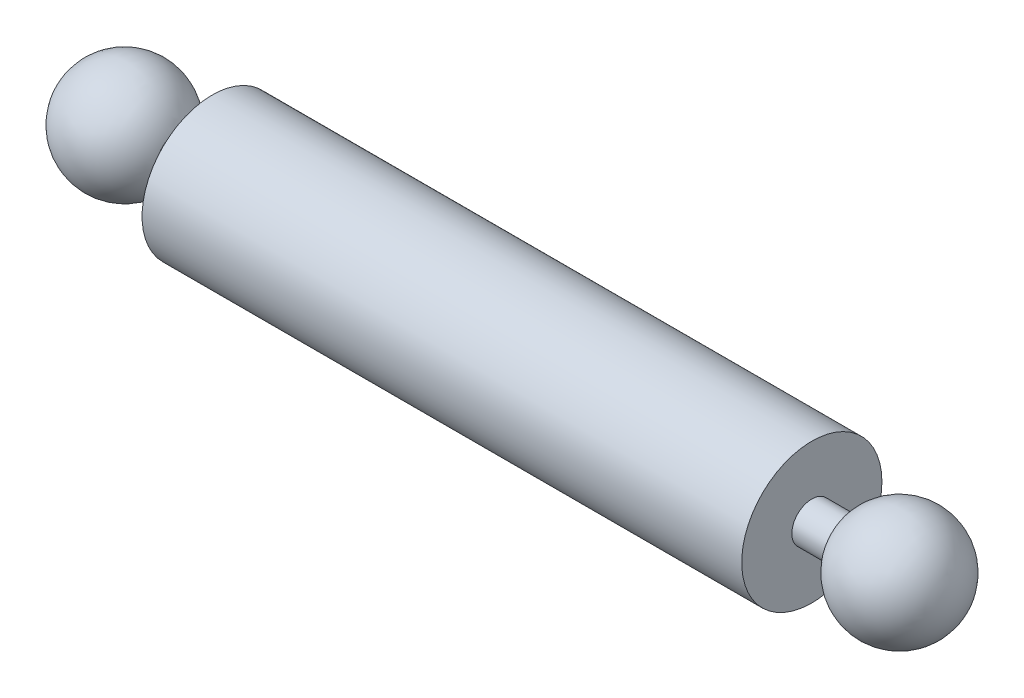
SolidWorks part; units mm, degrees
material "Chrome Stainless Steel"
ref_plane "Front Plane" through (0, 0, 0) normal (0, 0, 1) x (1, 0, 0)
ref_plane "Top Plane" through (0, 0, 0) normal (0, 1, 0) x (1, 0, 0)
ref_plane "Right Plane" through (0, 0, 0) normal (1, 0, 0) x (0, 0, -1)
sketch "Sketch1" plane through (0, 0, 0) normal (1, 0, 0) x (0, 0, -1)
  circle A0 centre (0, 0) radius 5.5689
  dimension "D1" = 11.1379
extrude "Boss-Extrude1" add sketch "Sketch1" against normal mid plane 47.625
sketch "Sketch2" plane through (-23.8125, 0, 0) normal (-1, 0, 0) x (0, 0, 1)
  circle A0 centre (0, 0) radius 1.5875
  dimension "D1" = 3.175
extrude "Boss-Extrude2" add sketch "Sketch2" along normal blind 3.175
sketch "Sketch5" plane through (0, 0, 0) normal (0, 0, 1) x (1, 0, 0)
  line L2 (-35.1917, 0) -> (-26.3525, 0)
  line L3 (-23.8125, 1.5875) -> (-23.8125, -1.5875) construction
  arc A3 (-26.3525, 0) -> (-35.1917, 0) centre (-30.7721, 0) ccw
  dimension "D1" = 2.54
  dimension "D2" = 4.4196
revolve "Revolve1" add sketch "Sketch5" angle 360 about L2
mirror "Mirror2" about plane through (0, 0, 0) normal (1, 0, 0) of "Boss-Extrude2", "Revolve1"
